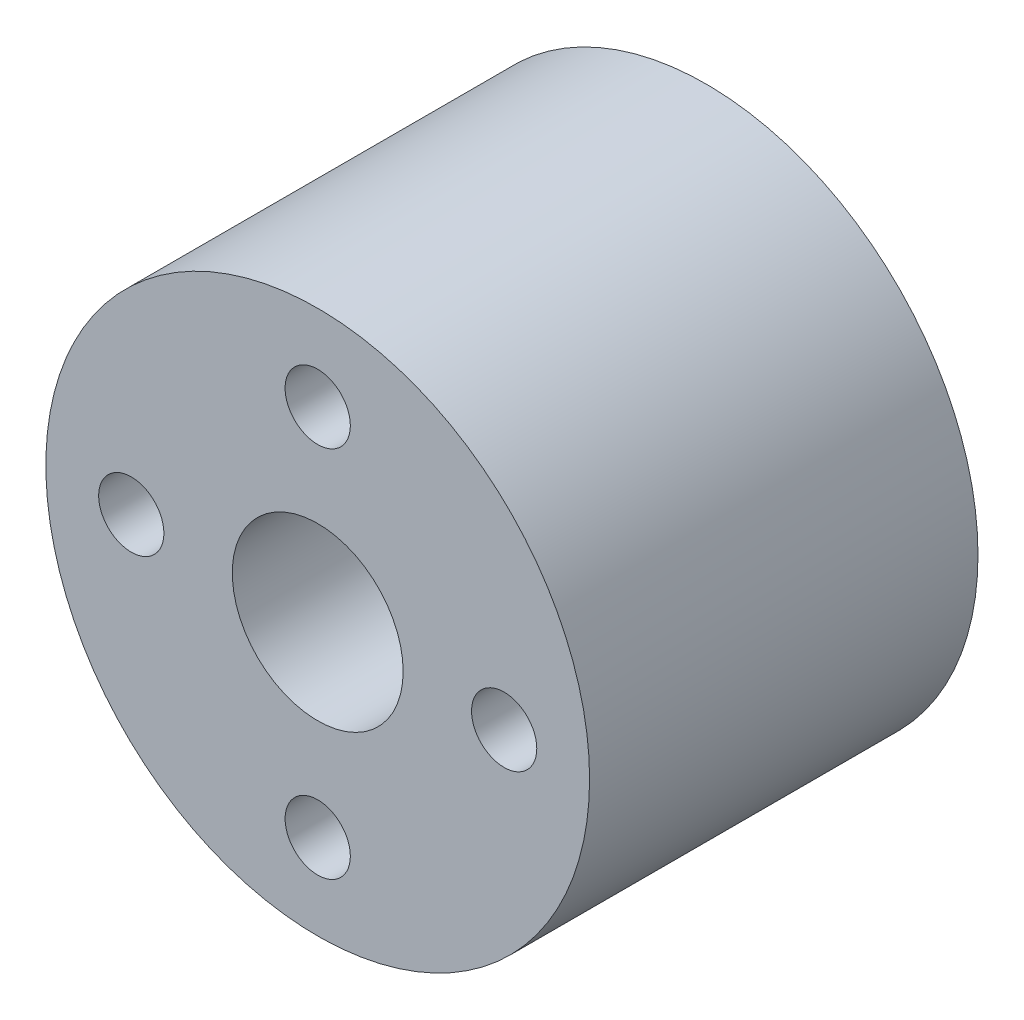
SolidWorks part; units mm, degrees
ref_plane "Front Plane" through (0, 0, 0) normal (0, 0, 1) x (1, 0, 0)
ref_plane "Top Plane" through (0, 0, 0) normal (0, 1, 0) x (1, 0, 0)
ref_plane "Right Plane" through (0, 0, 0) normal (1, 0, 0) x (0, 0, -1)
sketch "Sketch1" plane through (0, 0, 0) normal (0, 0, 1) x (1, 0, 0)
  circle A0 centre (0, 0) radius 60
  circle A14 centre (25, 0) radius 5.5
  circle A21 centre (-25, 0) radius 9
  dimension "D1" = 120
  dimension "D2" = 18
  dimension "D3" = 11
extrude "Boss-Extrude1" add sketch "Sketch1" against normal blind 25
sketch "Sketch6" plane through (0, 0, 0) normal (0, 0, 1) x (1, 0, 0)
  circle A1 centre (25, 12) radius 2.1
  dimension "D1" = 4.2
sketch "Sketch2" plane through (0, 0, 0) normal (0, 0, 1) x (1, 0, 0)
  circle A0 centre (0, 0) radius 63
  circle A1 centre (0, 0) radius 60 construction
  circle A2 centre (0, 0) radius 60
  dimension "D1" = 3
extrude "Cut-Extrude7" cut sketch "Sketch6" against normal up to next
pattern_circular "CirPattern4" count 4 over 360 about axis through (25, 0, 0) along (0, 0, 1) of "Cut-Extrude7"
extrude "Boss-Extrude2" add sketch "Sketch2" against normal blind 300
sketch "Sketch3" plane through (0, 0, -25) normal (0, 0, -1) x (-1, 0, 0)
  circle A1 centre (25, 0) radius 5 construction
  circle A2 centre (25, 0) radius 11.04
  dimension "D1" = 22.08
extrude "Cut-Extrude1" cut sketch "Sketch3" against normal blind 10
sketch "Sketch4" plane through (0, 0, 0) normal (0, 0, 1) x (1, 0, 0)
  circle A0 centre (-39, 0) radius 1.5 construction
  circle A1 centre (-39, 0) radius 1.5
extrude "Cut-Extrude2" cut sketch "Sketch4" against normal up to next
pattern_circular "CirPattern1" count 4 over 360 about axis through (-25, 0, 0) along (0, 0, 1) of "Cut-Extrude2"
sketch "Sketch5" plane through (0, 0, 0) normal (0, 0, 1) x (1, 0, 0)
  line L1 (-12.7321, -3) -> (-9.2679, -3)
  line L2 (-9.2679, -3) -> (-7.5359, 0)
  line L3 (-7.5359, 0) -> (-9.2679, 3)
  line L4 (-9.2679, 3) -> (-12.7321, 3)
  line L5 (-12.7321, 3) -> (-14.4641, 0)
  line L6 (-14.4641, 0) -> (-12.7321, -3)
  circle A5 centre (-11, 0) radius 1.5 construction
  circle A9 centre (-11, 0) radius 1.5 construction
  circle A10 centre (-11, 0) radius 3 construction
  point P0 (-8.4019, 1.5)
  dimension "D1" = 6
extrude "Cut-Extrude3" cut sketch "Sketch5" against normal blind 3
pattern_circular "CirPattern2" count 4 over 360 about axis through (-25, 0, 0) along (0, 0, 1) of "Cut-Extrude3"
sketch "Sketch7" plane through (0, 0, 0) normal (0, 0, 1) x (1, 0, 0)
  circle A0 centre (25, 0) radius 17.5
  circle A1 centre (25, 0) radius 5.5 construction
  point P3 (25, 0)
  point P4 (0, 0)
  dimension "D1" = 35
extrude "Cut-Extrude8" cut sketch "Sketch7" against normal through all flip side to cut
